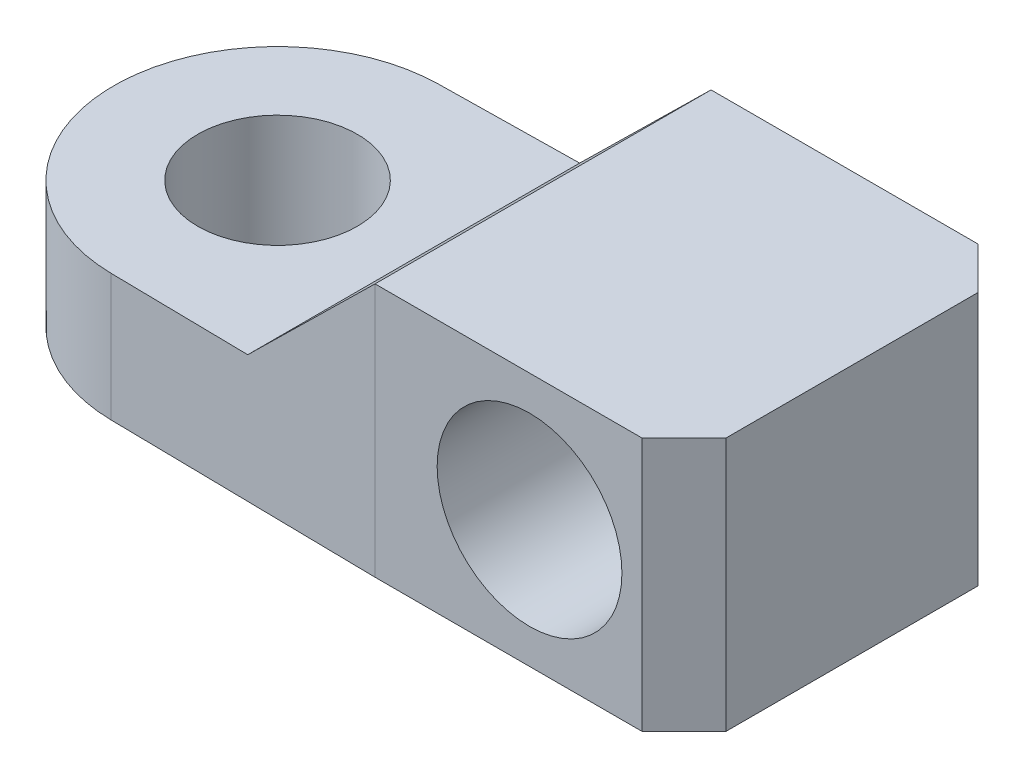
SolidWorks part; units mm, degrees
ref_plane "Front Plane" through (0, 0, 0) normal (0, 0, 1) x (1, 0, 0)
ref_plane "Top Plane" through (0, 0, 0) normal (0, 1, 0) x (1, 0, 0)
ref_plane "Right Plane" through (0, 0, 0) normal (1, 0, 0) x (0, 0, -1)
sketch "Sketch1" plane through (0, 0, 0) normal (0, 1, 0) x (1, 0, 0)
  line L0 (-0.0614, 3.8995) -> (6.322, 4)
  line L1 (6.322, 4) -> (13.678, 4)
  line L2 (13.678, 4) -> (13.678, -4)
  line L3 (13.678, -4) -> (6.322, -4)
  line L4 (6.322, -4) -> (-0.0614, -3.8995)
  line L5 (0, 0) -> (35.7724, 0) construction
  line L6 (10, -4) -> (10, 4) construction
  line L8 (9.322, -4) -> (10.678, -4) construction
  line L9 (9.322, -4) -> (9.322, 4) construction
  line L10 (9.322, 4) -> (10.678, 4) construction
  line L11 (10.678, -4) -> (10.678, 4) construction
  line L12 (9.322, -4) -> (10.678, 4) construction
  line L13 (9.322, 4) -> (10.678, -4) construction
  circle A0 centre (0, 0) radius 1.9
  arc A1 (-0.0614, 3.8995) -> (-0.0614, -3.8995) centre (0, 0) ccw
  point P6 (13.678, 0)
  point P14 (10, 0)
  point P18 (10, 0)
  dimension "D1" = 3.8
  dimension "D2" = 2
  dimension "D3" = 3
  dimension "D4" = 10
  dimension "D5" = 8
extrude "Boss-Extrude1" add sketch "Sketch1" along normal blind 6.05 contours A1 L4 L3 L2 L1 L0
sketch "Sketch2" plane through (0, 0, 0) normal (0, 0, 1) x (1, 0, 0)
  line L0 (10, 0) -> (10, 6.05) construction
  line L1 (13.678, 0) -> (6.322, 0) construction
  line L2 (13.678, 6.05) -> (6.322, 6.05) construction
  circle A0 centre (10, 3.025) radius 2.2
  dimension "D1" = 4.4
extrude "Cut-Extrude1" cut sketch "Sketch2" against normal blind 21 and the other way blind 19
chamfer "Chamfer2" distance 1 angle 45 4 edges at (13.678, 3.025, 4) (13.678, 3.025, -4) (13.678, 0, 0) (13.678, 6.05, 0)
sketch "Sketch3" plane through (0, 0, 0) normal (0, 0, 1) x (1, 0, 0)
  line L0 (-3.9, 3.025) -> (3.2419, 3.025)
  line L1 (-3.9, 6.05) -> (-3.9, 0) construction
  line L2 (3.2419, 3.025) -> (6.322, 6.05)
  line L3 (6.322, 6.05) -> (-0.0614, 6.05) construction
  line L4 (6.322, 6.05) -> (-3.9, 6.05)
  line L5 (-3.9, 6.05) -> (-3.9, 3.025)
  line L6 (6.322, 6.05) -> (6.322, 0) construction
extrude "Cut-Extrude2" cut sketch "Sketch3" against normal blind 10 and the other way blind 10
